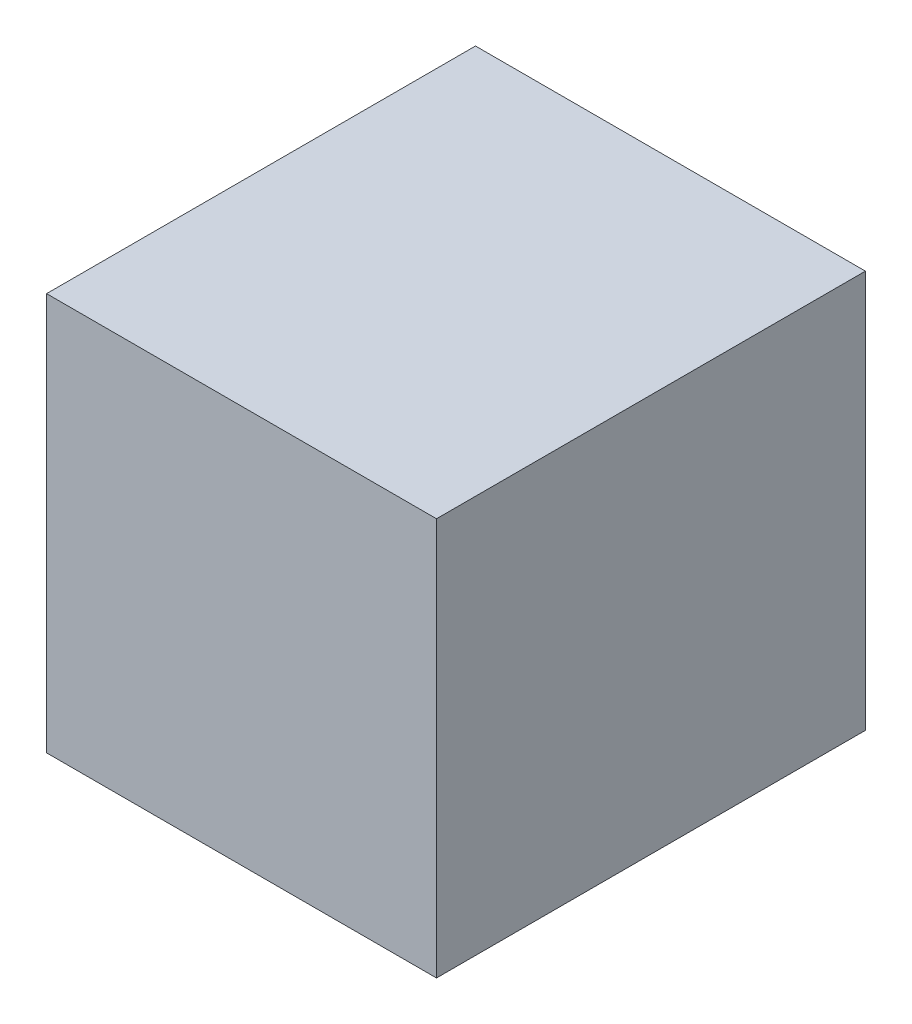
SolidWorks part; units mm, degrees
ref_plane "Front Plane" through (0, 0, 0) normal (0, 0, 1) x (1, 0, 0)
ref_plane "Top Plane" through (0, 0, 0) normal (0, 1, 0) x (1, 0, 0)
ref_plane "Right Plane" through (0, 0, 0) normal (1, 0, 0) x (0, 0, -1)
sketch "Sketch1" plane through (0, 0, 0) normal (0, 0, 1) x (1, 0, 0)
  line L1 (-25, 25.5) -> (25, 25.5)
  line L2 (-25, 25.5) -> (-25, -25.5)
  line L3 (-25, -25.5) -> (25, -25.5)
  line L4 (25, 25.5) -> (25, -25.5)
  line L5 (-25, 25.5) -> (25, -25.5) construction
  line L6 (-25, -25.5) -> (25, 25.5) construction
  point P0 (0, 0)
  dimension "D1" = 50
  dimension "D2" = 51
extrude "Boss-Extrude2" add sketch "Sketch1" along normal blind 5
sketch "Sketch3" plane through (25, 0, 0) normal (1, 0, 0) x (0, 0, -1)
  line L0 (-5, 25.5) -> (50, 25.5)
  line L1 (50, 25.5) -> (50, -25.5)
  line L2 (50, -25.5) -> (0, -25.5)
  line L7 (0, -25.5) -> (0, 25.5)
  line L8 (0, 25.5) -> (-5, 25.5)
  line L9 (-5, 25.5) -> (-5, -25.5)
  line L10 (-5, -25.5) -> (0, -25.5)
  line L13 (-5, 25.5) -> (-5, -25.5)
  line L14 (-5, -25.5) -> (0, -25.5)
  dimension "D1" = 55
  dimension "D2" = 51
  dimension "D3" = 0
extrude "Boss-Extrude3" add sketch "Sketch3" against normal blind 5
sketch "Sketch8" plane through (0, 25.5, 0) normal (0, 1, 0) x (1, 0, 0)
  line L1 (-25, -5) -> (25, -5)
  line L2 (-25, -5) -> (-25, 50)
  line L3 (-25, 50) -> (25, 50)
  line L4 (25, -5) -> (25, 50)
extrude "Boss-Extrude4" add sketch "Sketch8" against normal blind 5
sketch "Sketch13" plane through (-25, 0, 0) normal (-1, 0, 0) x (0, 0, 1)
  line L0 (5, -25.5) -> (-50, -25.5)
  line L1 (-50, -25.5) -> (-50, 25.5)
  line L2 (-50, 20.5) -> (-50, 25.5) construction
  line L3 (-50, 25.5) -> (5, 25.5)
  line L4 (5, 25.5) -> (5, -25.5)
extrude "Boss-Extrude5" add sketch "Sketch13" against normal blind 5
sketch "Sketch14" plane through (0, -25.5, 0) normal (0, -1, 0) x (1, 0, 0)
  line L0 (-25, 5) -> (-25, -50)
  line L1 (-25, -50) -> (25, -50)
  line L2 (25, -50) -> (25, 5)
  line L3 (25, 5) -> (-25, 5)
extrude "Boss-Extrude6" add sketch "Sketch14" against normal blind 5
